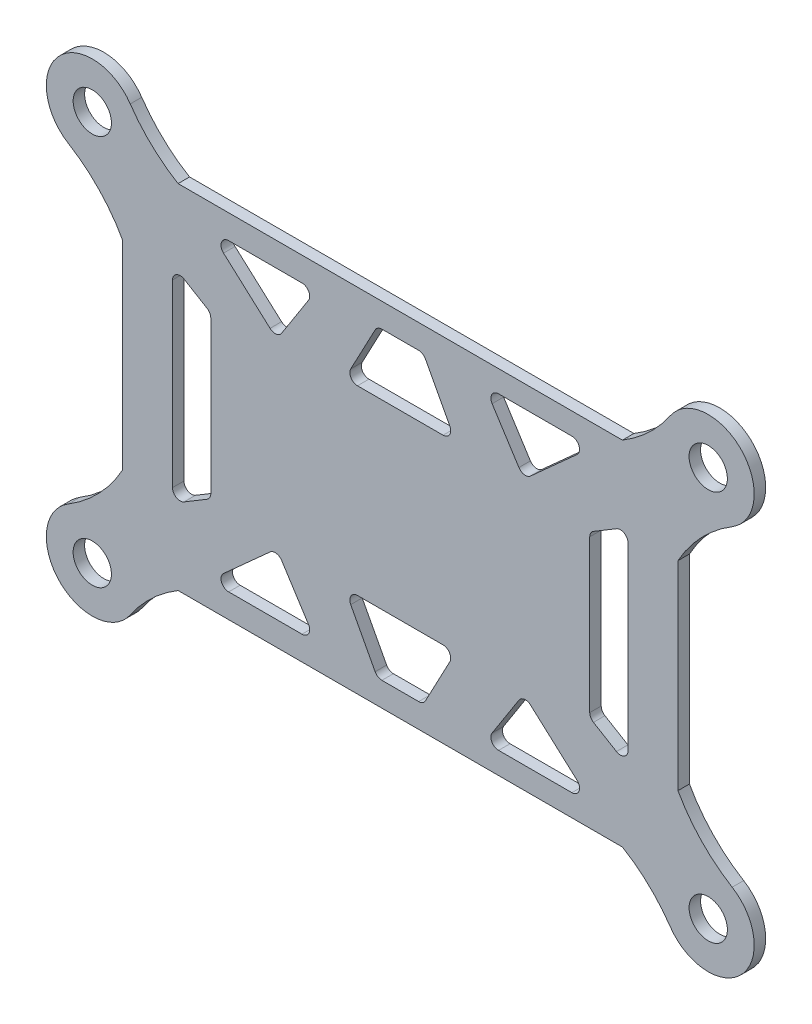
SolidWorks part; units mm, degrees
ref_plane "Front Plane" through (0, 0, 0) normal (0, 0, 1) x (1, 0, 0)
ref_plane "Top Plane" through (0, 0, 0) normal (0, 1, 0) x (1, 0, 0)
ref_plane "Right Plane" through (0, 0, 0) normal (1, 0, 0) x (0, 0, -1)
sketch "Sketch1" plane through (0, 0, 0) normal (0, 0, 1) x (1, 0, 0)
  line L0 (-36.25, -13) -> (-36.25, 13)
  line L1 (-29, 23) -> (29, 23)
  line L2 (-29, -23) -> (29, -23)
  line L3 (36.25, -13) -> (36.25, 13)
  line L4 (-36.25, 0) -> (36.25, 0) construction
  line L5 (0, 23) -> (0, -23) construction
  arc A0 (-35.2447, 28.8831) -> (-43.3255, 20.3783) centre (-40.2, 25.5) ccw
  arc A1 (-36.25, 13) -> (-43.3255, 20.3783) centre (-53.7437, 3.3061) ccw
  arc A2 (-35.2447, 28.8831) -> (-29, 23) centre (-18.7272, 40.1601) ccw
  arc A3 (-36.25, -13) -> (-43.3255, -20.3783) centre (-53.7437, -3.3061) cw
  arc A4 (-35.2447, -28.8831) -> (-29, -23) centre (-18.7272, -40.1601) cw
  arc A5 (-35.2447, -28.8831) -> (-43.3255, -20.3783) centre (-40.2, -25.5) cw
  arc A6 (35.2447, -28.8831) -> (29, -23) centre (18.7272, -40.1601) ccw
  arc A7 (35.2447, -28.8831) -> (43.3255, -20.3783) centre (40.2, -25.5) ccw
  arc A8 (36.25, -13) -> (43.3255, -20.3783) centre (53.7437, -3.3061) ccw
  arc A9 (36.25, 13) -> (43.3255, 20.3783) centre (53.7437, 3.3061) cw
  arc A10 (35.2447, 28.8831) -> (29, 23) centre (18.7272, 40.1601) cw
  arc A11 (35.2447, 28.8831) -> (43.3255, 20.3783) centre (40.2, 25.5) cw
  point P3 (-36.25, 0)
  point P10 (36.25, 0)
  point P12 (0, 23)
  point P16 (0, -23)
  dimension "D8" = 12
  dimension "D9" = 40
  dimension "D10" = 40
  dimension "D1" = 72.5
  dimension "D2" = 26
  dimension "D3" = 58
  dimension "D4" = 10
  dimension "D5" = 10
  dimension "D6" = 12.5
  dimension "D7" = 3.95
extrude "Boss-Extrude1" add sketch "Sketch1" along normal blind 1.5
sketch "Sketch2" plane through (0, 0, 1.5) normal (0, 0, 1) x (1, 0, 0)
  line L0 (0, 0) -> (18.1323, 0) construction
  line L1 (0, 0) -> (0, 14.7378) construction
  line L2 (-22.3964, 19.85) -> (-12.8264, 19.85)
  line L3 (-11.9841, 18.311) -> (-15.4823, 12.8445)
  line L4 (-16.9937, 12.6403) -> (-23.0655, 18.1068)
  line L5 (-29.7335, 11.735) -> (-29.7335, -11.735)
  line L6 (-28.2192, -12.5926) -> (-25.2175, -10.7926)
  line L7 (-24.7318, -9.935) -> (-24.7318, 9.935)
  line L8 (-25.2175, 10.7926) -> (-28.2192, 12.5926)
  line L9 (-2.3964, 19.85) -> (2.4036, 19.85)
  line L10 (3.2867, 19.3191) -> (6.4717, 13.3224)
  line L11 (5.5886, 11.8533) -> (-5.5814, 11.8533)
  line L12 (-6.4646, 13.3224) -> (-3.2796, 19.3191)
  line L13 (22.4036, 20.1517) -> (12.8336, 20.1517)
  line L14 (11.9913, 18.6127) -> (15.4895, 13.1462)
  line L15 (17.0009, 12.9421) -> (23.0727, 18.4085)
  line L16 (29, 23) -> (-29, 23) construction
  line L17 (-36.25, 13) -> (-36.25, -13) construction
  line L18 (17.0009, -12.9421) -> (23.0727, -18.4085)
  line L19 (11.9913, -18.6127) -> (15.4895, -13.1462)
  line L20 (22.4036, -20.1517) -> (12.8336, -20.1517)
  line L21 (-6.4646, -13.3224) -> (-3.2796, -19.3191)
  line L22 (5.5886, -11.8533) -> (-5.5814, -11.8533)
  line L23 (3.2867, -19.3191) -> (6.4717, -13.3224)
  line L24 (-2.3964, -19.85) -> (2.4036, -19.85)
  line L25 (-16.9937, -12.6403) -> (-23.0655, -18.1068)
  line L26 (-11.9841, -18.311) -> (-15.4823, -12.8445)
  line L27 (-22.3964, -19.85) -> (-12.8264, -19.85)
  line L28 (25.2175, 10.7926) -> (28.2192, 12.5926)
  line L29 (24.7318, -9.935) -> (24.7318, 9.935)
  line L30 (28.2192, -12.5926) -> (25.2175, -10.7926)
  line L31 (29.7335, 11.735) -> (29.7335, -11.735)
  circle A0 centre (-40.2, 25.5) radius 2.5
  circle A1 centre (-40.2, -25.5) radius 2.5
  circle A2 centre (40.2, -25.5) radius 2.5
  circle A3 centre (40.2, 25.5) radius 2.5
  arc A4 (-29.7335, 11.735) -> (-28.2192, 12.5926) centre (-28.7335, 11.735) cw
  arc A5 (-24.7318, 9.935) -> (-25.2175, 10.7926) centre (-25.7318, 9.935) ccw
  arc A6 (-25.2175, -10.7926) -> (-24.7318, -9.935) centre (-25.7318, -9.935) ccw
  arc A7 (-29.7335, -11.735) -> (-28.2192, -12.5926) centre (-28.7335, -11.735) ccw
  arc A8 (22.4036, 20.1517) -> (23.0727, 18.4085) centre (22.4036, 19.1517) cw
  arc A9 (12.8336, 20.1517) -> (11.9913, 18.6127) centre (12.8336, 19.1517) ccw
  arc A10 (15.4895, 13.1462) -> (17.0009, 12.9421) centre (16.3318, 13.6852) ccw
  arc A11 (6.4717, 13.3224) -> (5.5886, 11.8533) centre (5.5886, 12.8533) cw
  arc A12 (2.4036, 19.85) -> (3.2867, 19.3191) centre (2.4036, 18.85) cw
  arc A13 (-2.3964, 19.85) -> (-3.2796, 19.3191) centre (-2.3964, 18.85) ccw
  arc A14 (-5.5814, 11.8533) -> (-6.4646, 13.3224) centre (-5.5814, 12.8533) cw
  arc A15 (-12.8264, 19.85) -> (-11.9841, 18.311) centre (-12.8264, 18.85) cw
  arc A16 (-15.4823, 12.8445) -> (-16.9937, 12.6403) centre (-16.3246, 13.3835) cw
  arc A17 (-22.3964, 19.85) -> (-23.0655, 18.1068) centre (-22.3964, 18.85) ccw
  arc A18 (6.4717, -13.3224) -> (5.5886, -11.8533) centre (5.5886, -12.8533) ccw
  arc A19 (-5.5814, -11.8533) -> (-6.4646, -13.3224) centre (-5.5814, -12.8533) ccw
  arc A20 (-22.3964, -19.85) -> (-23.0655, -18.1068) centre (-22.3964, -18.85) cw
  arc A21 (-15.4823, -12.8445) -> (-16.9937, -12.6403) centre (-16.3246, -13.3835) ccw
  arc A22 (-12.8264, -19.85) -> (-11.9841, -18.311) centre (-12.8264, -18.85) ccw
  arc A23 (-2.3964, -19.85) -> (-3.2796, -19.3191) centre (-2.3964, -18.85) cw
  arc A24 (2.4036, -19.85) -> (3.2867, -19.3191) centre (2.4036, -18.85) ccw
  arc A25 (15.4895, -13.1462) -> (17.0009, -12.9421) centre (16.3318, -13.6852) cw
  arc A26 (12.8336, -20.1517) -> (11.9913, -18.6127) centre (12.8336, -19.1517) cw
  arc A27 (22.4036, -20.1517) -> (23.0727, -18.4085) centre (22.4036, -19.1517) ccw
  arc A28 (29.7335, -11.735) -> (28.2192, -12.5926) centre (28.7335, -11.735) cw
  arc A29 (25.2175, -10.7926) -> (24.7318, -9.935) centre (25.7318, -9.935) cw
  arc A30 (24.7318, 9.935) -> (25.2175, 10.7926) centre (25.7318, 9.935) cw
  arc A31 (29.7335, 11.735) -> (28.2192, 12.5926) centre (28.7335, 11.735) ccw
  point P51 (-10.9992, 19.85)
  point P60 (-36.25, 0)
  point P61 (-29.7335, 0)
  point P62 (-23.33, 19.2083)
  point P93 (-10.9992, -19.85)
  dimension "D1" = 5
  dimension "D2" = 1
  dimension "D3" = 8.17
  dimension "9.75" = 9.57
  dimension "D4" = 6.49
  dimension "D5" = 3.15
  dimension "D6" = 23.47
  dimension "D7" = 3.5
  dimension "D8" = 19.87
  dimension "D9" = 16.87
  dimension "D10" = 11.17
  dimension "D11" = 4.8
  dimension "D12" = 6.79
  dimension "D13" = 9.57
  dimension "D14" = 6.49
  dimension "D15" = 8.17
  dimension "D16" = 10.43
  dimension "D17" = 10.43
extrude "Cut-Extrude1" cut sketch "Sketch2" against normal through all
